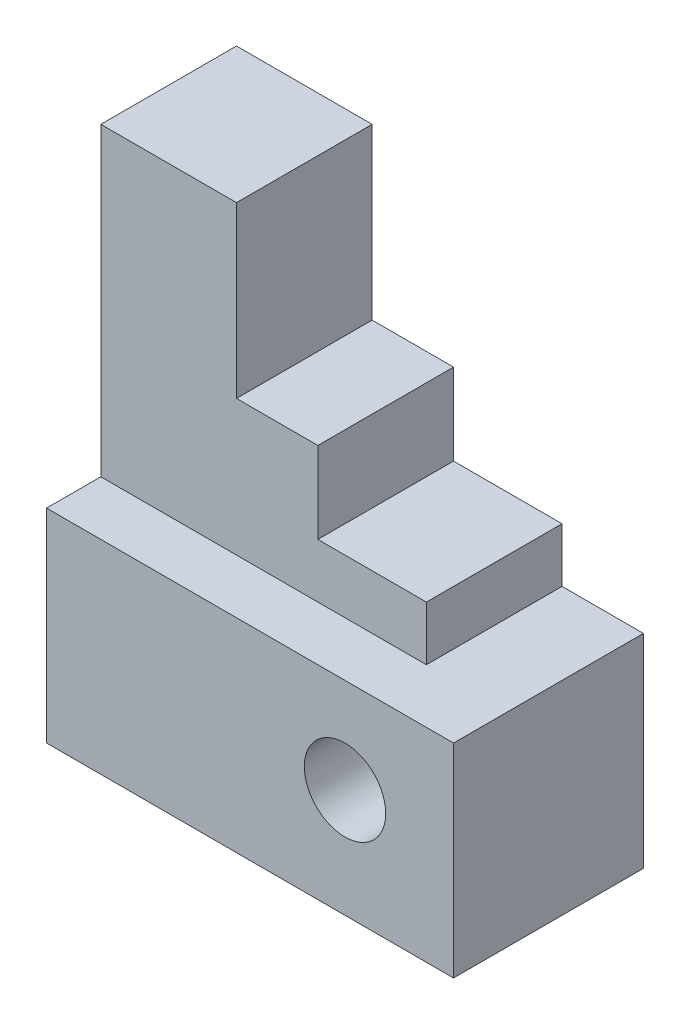
SolidWorks part; units mm, degrees
ref_plane "Front Plane" through (0, 0, 0) normal (0, 0, 1) x (1, 0, 0)
ref_plane "Top Plane" through (0, 0, 0) normal (0, 1, 0) x (1, 0, 0)
ref_plane "Right Plane" through (0, 0, 0) normal (1, 0, 0) x (0, 0, -1)
other "Configuration Table"
sketch "Sketch1" plane through (0, 0, 0) normal (0, 0, 1) x (1, 0, 0)
  line L1 (0, 0) -> (60, 0)
  line L2 (0, 0) -> (0, 75)
  line L3 (0, 75) -> (60, 75)
  line L4 (60, 0) -> (60, 75)
  dimension "D1" = 75
  dimension "D2" = 60
extrude "Boss-Extrude1" add sketch "Sketch1" along normal mid plane 28
sketch "Sketch2" plane through (0, 0, 0) normal (0, 0, 1) x (1, 0, 0)
  line L0 (60, 75) -> (0, 75) construction
  line L1 (20, 75) -> (60, 75)
  line L2 (20, 75) -> (20, 50)
  line L3 (20, 50) -> (60, 50)
  line L4 (60, 75) -> (60, 50)
  line L5 (60, 0) -> (60, 75) construction
  line L6 (0, 75) -> (0, 0) construction
  line L7 (32, 50) -> (60, 50)
  line L8 (32, 50) -> (32, 38)
  line L9 (32, 38) -> (60, 38)
  line L10 (60, 50) -> (60, 38)
  line L11 (48, 38) -> (60, 38)
  line L12 (48, 38) -> (48, 30)
  line L13 (48, 30) -> (60, 30)
  line L14 (60, 38) -> (60, 30)
  line L15 (0, 0) -> (60, 0) construction
  circle A0 centre (44, 16) radius 6
  dimension "D7" = 12
  dimension "D1" = 20
  dimension "D2" = 30
  dimension "D3" = 12
  dimension "D4" = 20
  dimension "D5" = 12
  dimension "D6" = 12
  dimension "D8" = 16
  dimension "D9" = 16
extrude "Cut-Extrude3" cut sketch "Sketch2" against normal through all both and the other way through all contours L4 L1 L2 L3 | L10 L3 L8 L9 | L14 L9 L12 L13 | A0
sketch "Sketch3" plane through (0, 30, 0) normal (0, 1, 0) x (1, 0, 0)
  line L0 (48, 14) -> (48, -14) construction
  line L1 (0, 14) -> (48, 14)
  line L2 (0, 14) -> (0, -6)
  line L3 (0, -6) -> (48, -6)
  line L4 (48, 14) -> (48, -6)
  dimension "D1" = 20
extrude "Cut-Extrude4" cut sketch "Sketch3" along normal through all flip side to cut
equation "\"GAUGE\"= SWITCH ( \"Thickness\" < 0.9 , 0 , \"Thickness\" < 1.1 , 20 , \"Thickness\" < 1.6 , 16 , \"Thickness\" < 2.1 , 14 , \"Thickness\" < 3.1 , 11 , \"Thickness\" < 4.8 , 7 , \"Thickness\" > 4.8 , 0 )"
